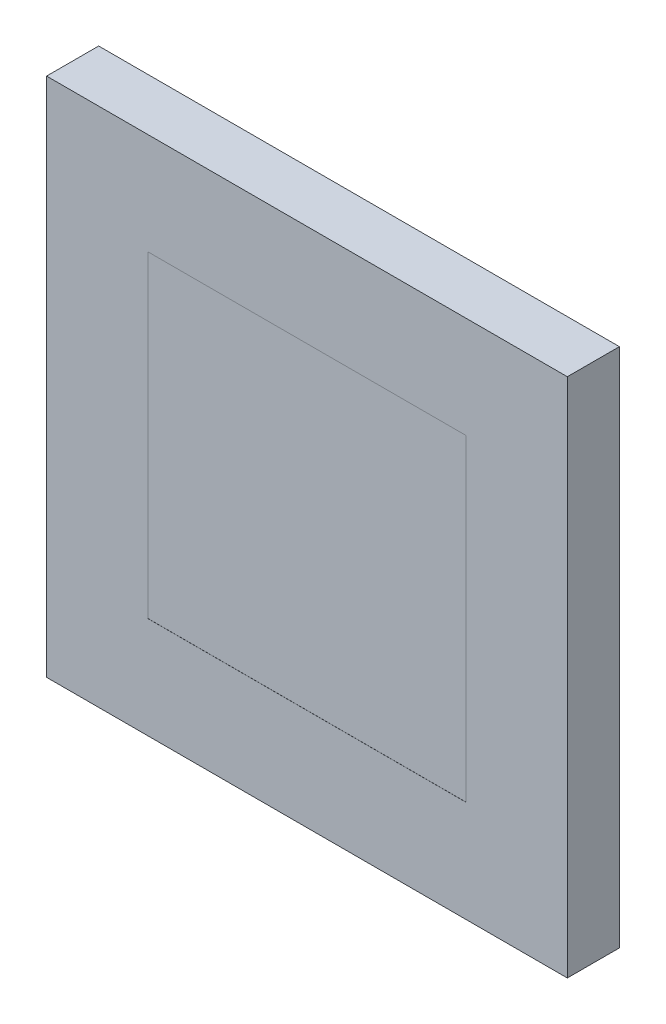
SolidWorks part; units mm, degrees
ref_plane "Front Plane" through (0, 0, 0) normal (0, 0, 1) x (1, 0, 0)
ref_plane "Top Plane" through (0, 0, 0) normal (0, 1, 0) x (1, 0, 0)
ref_plane "Right Plane" through (0, 0, 0) normal (1, 0, 0) x (0, 0, -1)
sketch "Sketch1" plane through (0, 0, 0) normal (0, 0, 1) x (1, 0, 0)
  line L1 (0, 0) -> (500, 0)
  line L2 (0, 0) -> (0, 500)
  line L3 (0, 500) -> (500, 500)
  line L4 (500, 0) -> (500, 500)
  dimension "D1" = 500
extrude "Boss-Extrude1" add sketch "Sketch1" along normal blind 50
sketch "Sketch2" plane through (0, 0, 50) normal (0, 0, 1) x (1, 0, 0)
  line L0 (0, -27.5) -> (0, 27.5) construction
  line L1 (97.5, 97.5) -> (402.5, 97.5)
  line L2 (97.5, 97.5) -> (97.5, 402.5)
  line L3 (97.5, 402.5) -> (402.5, 402.5)
  line L4 (402.5, 97.5) -> (402.5, 402.5)
  line L5 (500, 500) -> (0, 500) construction
  dimension "D1" = 305
  dimension "D2" = 97.5
  dimension "D3" = 97.5
extrude "Cut-Extrude1" cut sketch "Sketch2" against normal blind 0.1
